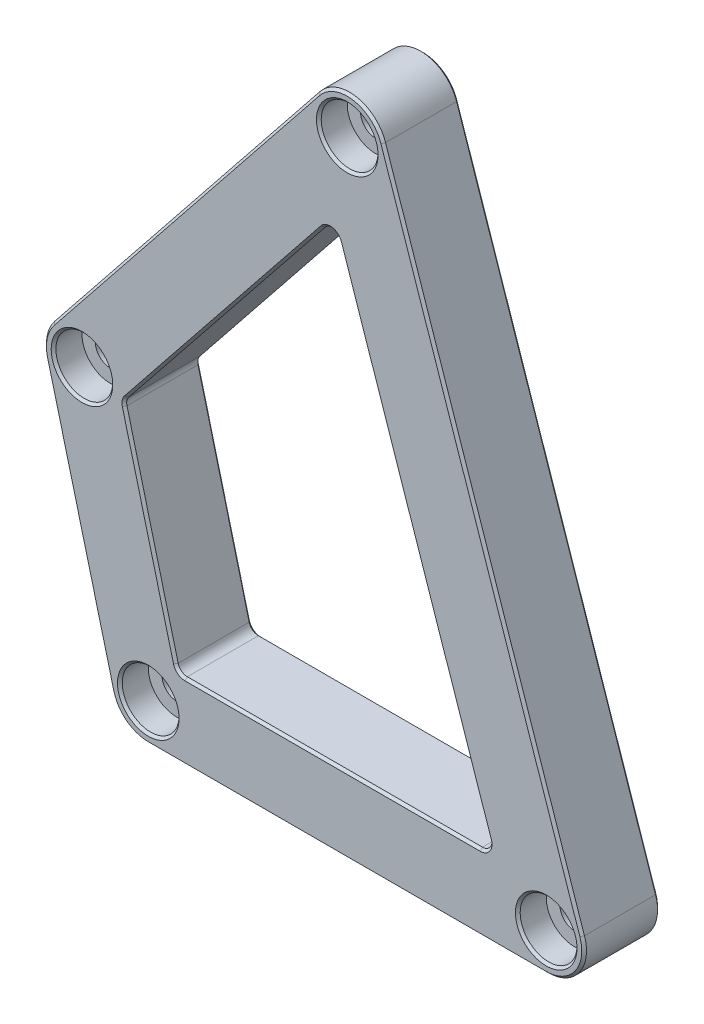
SolidWorks part; units mm, degrees
ref_plane "Płaszczyzna przednia" through (0, 0, 0) normal (0, 0, 1) x (1, 0, 0)
ref_plane "Płaszczyzna górna" through (0, 0, 0) normal (0, 1, 0) x (1, 0, 0)
ref_plane "Płaszczyzna prawa" through (0, 0, 0) normal (1, 0, 0) x (0, 0, -1)
sketch "Szkic1" plane through (0, 0, 0) normal (0, 0, 1) x (1, 0, 0)
  line L0 (-21, -62) -> (21, -62) construction
  line L1 (0, -62) -> (0, 0) construction
  line L2 (-21, -62) -> (-28, -35) construction
  line L3 (-28, -35) -> (0, 0) construction
  line L4 (0, 0) -> (21, -62) construction
  line L5 (-32.3746, -34.0651) -> (1.4433, 8.2073)
  line L6 (1.4433, 8.2073) -> (26.5781, -66)
  line L7 (-24.0952, -66) -> (26.5781, -66)
  line L8 (-24.0952, -66) -> (-32.3746, -34.0651)
  line L9 (-23.6254, -35.9349) -> (-1.4433, -8.2073)
  line L10 (-1.4433, -8.2073) -> (15.4219, -58)
  line L11 (-17.9048, -58) -> (15.4219, -58)
  line L12 (-17.9048, -58) -> (-23.6254, -35.9349)
  circle A0 centre (-21, -62) radius 1.55
  circle A1 centre (21, -62) radius 1.55
  circle A2 centre (0, 0) radius 1.6
  circle A3 centre (-28, -35) radius 1.6
  point P0 (0, 0)
  point P1 (-28, -35)
  point P3 (-21, -62)
  point P4 (21, -62)
  dimension "D5" = 3.2
  dimension "D6" = 3.1
  dimension "D1" = 28
  dimension "D2" = 35
  dimension "D3" = 42
  dimension "D4" = 62
  dimension "D7" = 4
  dimension "D8" = 4
extrude "Dodanie-wyciągnięcie1" add sketch "Szkic1" along normal blind 8
fillet "Zaokrąglenie1" radius 4 4 edges at (-24.0952, -66, 4) (-32.3746, -34.0651, 4) (26.5781, -66, 4) (1.4433, 8.2073, 4)
sketch "Szkic2" plane through (0, 0, 8) normal (0, 0, 1) x (1, 0, 0)
  circle A0 centre (0, 0) radius 3
  circle A1 centre (-28, -35) radius 3
  circle A2 centre (-21, -62) radius 3
  circle A3 centre (21, -62) radius 3
  dimension "D1" = 6
extrude "Wytnij-wyciągnięcie1" cut sketch "Szkic2" against normal blind 3
fillet "Zaokrąglenie2" radius 1 4 edges at (15.4219, -58, 4) (-17.9048, -58, 4) (-23.6254, -35.9349, 4) (-1.4433, -8.2073, 4)
chamfer "Sfazowanie1" distance 0.25 angle 45 36 edges at (7.0588, -33.3087, 0) (-1.631, -9.2742, 0) (14.8401, -57.5827, 0) (-12.9488, -22.5891, 0) (-1.5518, -58, 0) (-23.5097, -35.9596, 0) (-17.743, -57.7909, 0) (-20.7994, -46.8352, 0) (7.0588, -33.3087, 8) (-1.631, -9.2742, 8) (14.8401, -57.5827, 8) (-12.9488, -22.5891, 8) (-1.5518, -58, 8) (-23.5097, -35.9596, 8) (-17.743, -57.7909, 8) (-20.7994, -46.8352, 8) (14.2886, -29.7168, 8) (0.6928, 3.9395, 8) (24.2506, -64.331, 8) (-17.1235, -15.0012, 8) (0, -66, 8) (-31.9117, -34.1641, 8) (-23.4479, -65.1635, 8) (-28.372, -49.5038, 8) (14.2886, -29.7168, 0) (0.6928, 3.9395, 0) (24.2506, -64.331, 0) (-17.1235, -15.0012, 0) (0, -66, 0) (-31.9117, -34.1641, 0) (-23.4479, -65.1635, 0) (-28.372, -49.5038, 0) (24, -62, 8) (-18, -62, 8) (-25, -35, 8) (3, 0, 8)
sketch "Szkic3" plane through (0, 0, 0) normal (0, 0, -1) x (-1, 0, 0)
  line L0 (-21, -62) -> (-11, -62) construction
  line L1 (-11, -60.5) -> (-11, -63.5)
  line L2 (-11, -63.5) -> (-7.2919, -62)
  line L3 (-7.2919, -62) -> (-11, -60.5)
  dimension "D1" = 10
  dimension "D2" = 3
  dimension "D3" = 4
extrude "Wytnij-wyciągnięcie2" cut sketch "Szkic3" against normal blind 1
